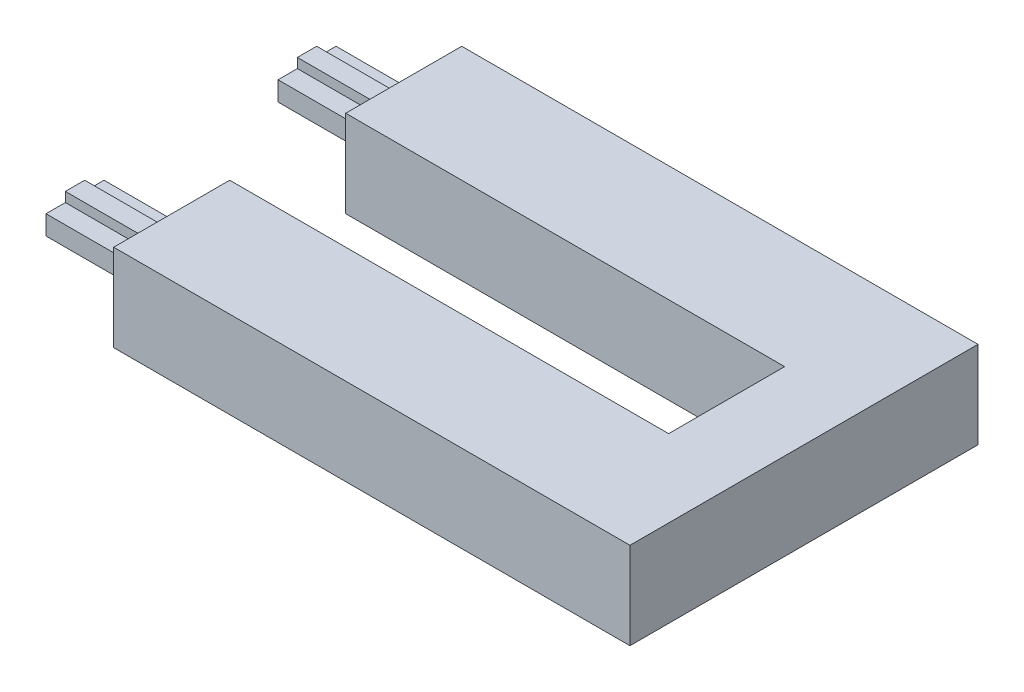
SolidWorks part; units mm, degrees
ref_plane "Front Plane" through (0, 0, 0) normal (0, 0, 1) x (1, 0, 0)
ref_plane "Top Plane" through (0, 0, 0) normal (0, 1, 0) x (1, 0, 0)
ref_plane "Right Plane" through (0, 0, 0) normal (1, 0, 0) x (0, 0, -1)
sketch "Sketch1" plane through (0, 0, 0) normal (0, 1, 0) x (1, 0, 0)
  line L0 (0, 12) -> (0, 18)
  line L1 (0, 0) -> (26.7, 0)
  line L2 (0, 0) -> (0, 6)
  line L3 (0, 18) -> (26.7, 18)
  line L4 (26.7, 0) -> (26.7, 18)
  line L5 (0, 0) -> (26.7, 18) construction
  line L6 (0, 18) -> (26.7, 0) construction
  line L8 (0, 12) -> (22.7, 12)
  line L10 (0, 6) -> (22.7, 6)
  line L11 (22.7, 12) -> (22.7, 6)
  line L12 (0, 12) -> (22.7, 6) construction
  line L13 (0, 6) -> (22.7, 12) construction
  point P4 (13.35, 9)
  point P12 (11.35, 9)
  dimension "D1" = 18
  dimension "D2" = 26.7
  dimension "D3" = 6
  dimension "D4" = 6
  dimension "D5" = 4
extrude "Boss-Extrude1" add sketch "Sketch1" along normal blind 4.5
sketch "Sketch2" plane through (0, 0, 0) normal (-1, 0, 0) x (0, 0, 1)
  line L0 (-16.5, 2.25) -> (-13.5, 2.25)
  line L1 (-18, 4.5) -> (-18, 0) construction
  line L2 (-18, 4.5) -> (-12, 4.5) construction
  line L3 (-15, 1.25) -> (-15, 3.25)
  line L4 (-9, 4.5) -> (-9, 0) construction
  line L5 (-12, 4.5) -> (-6, 4.5) construction
  line L6 (-12, 0) -> (-6, 0) construction
  line L7 (-3, 1.25) -> (-3, 3.25)
  line L8 (-1.5, 2.25) -> (-4.5, 2.25)
  point P9 (-15, 2.25)
  dimension "D1" = 3
  dimension "D2" = 1.5
  dimension "D3" = 2.25
  dimension "D4" = 2
extrude "Cut-Extrude-Thin1" [suppressed] cut sketch "Sketch2" against normal blind 5 thin
sketch "Sketch3" plane through (0, 0, 0) normal (-1, 0, 0) x (0, 0, 1)
  line L0 (-16.5, 2.25) -> (-13.5, 2.25)
  line L3 (-15, 1.25) -> (-15, 3.25)
  line L4 (-9, 4.5) -> (-9, 0) construction
  line L7 (-3, 1.25) -> (-3, 3.25)
  line L8 (-1.5, 2.25) -> (-4.5, 2.25)
  point P9 (-15, 2.25)
  dimension "D1" = 3
  dimension "D4" = 2
extrude "Extrude-Thin1" add sketch "Sketch3" along normal blind 5 thin thin type mid plane wall 1
